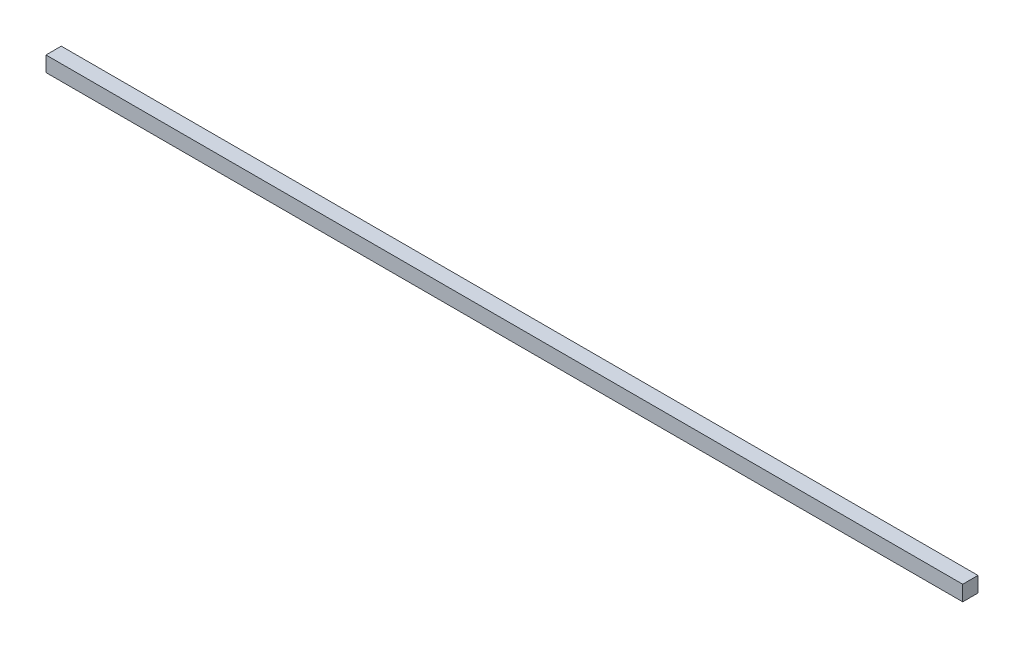
SolidWorks part; units mm, degrees
ref_plane "前视基准面" through (0, 0, 0) normal (0, 0, 1) x (1, 0, 0)
ref_plane "上视基准面" through (0, 0, 0) normal (0, 1, 0) x (1, 0, 0)
ref_plane "右视基准面" through (0, 0, 0) normal (1, 0, 0) x (0, 0, -1)
sketch "草图1" plane through (0, 0, 0) normal (0, 1, 0) x (1, 0, 0)
  line L1 (-600, 220) -> (600, 220)
  line L2 (-600, 220) -> (-600, 200)
  line L3 (-600, 200) -> (600, 200)
  line L4 (600, 220) -> (600, 200)
  line L5 (-600, 220) -> (600, 200) construction
  line L6 (-600, 200) -> (600, 220) construction
  point P0 (0, 210)
  dimension "D1" = 1200
  dimension "D2" = 20
  dimension "D3" = 200
extrude "凸台-拉伸1" add sketch "草图1" along normal blind 20
